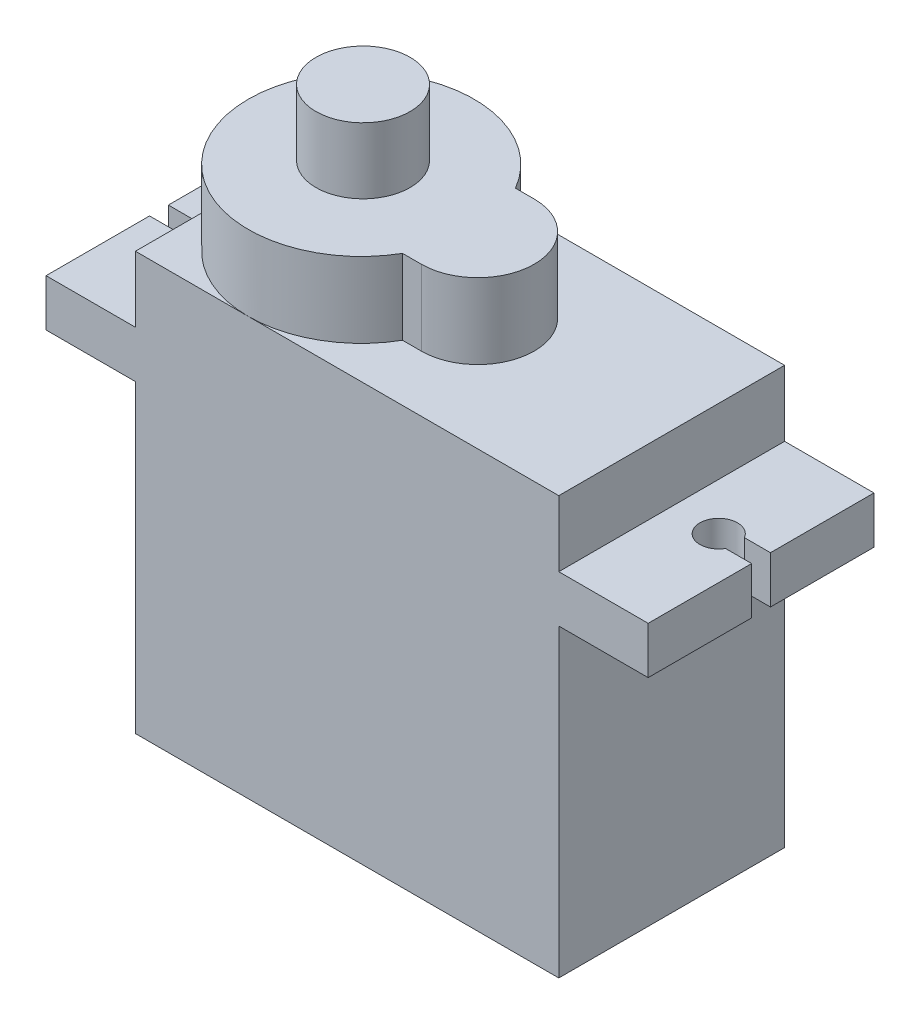
SolidWorks part; units mm, degrees
ref_plane "Front Plane" through (0, 0, 0) normal (0, 0, 1) x (1, 0, 0)
ref_plane "Top Plane" through (0, 0, 0) normal (0, 1, 0) x (1, 0, 0)
ref_plane "Right Plane" through (0, 0, 0) normal (1, 0, 0) x (0, 0, -1)
sketch "Sketch1" plane through (0, 0, 0) normal (0, 0, 1) x (1, 0, 0)
  line L0 (11.25, 0) -> (-11.25, 0)
  line L1 (11.25, 0) -> (11.25, 22.2)
  line L2 (-11.25, 0) -> (-11.25, 22.2)
  line L3 (11.25, 22.2) -> (-11.25, 22.2)
  dimension "D1" = 22.2
  dimension "D2" = 22.5
extrude "Boss-Extrude1" add sketch "Sketch1" along normal mid plane 12
sketch "Sketch2" plane through (0, 22.2, 0) normal (0, 1, 0) x (1, 0, 0)
  line L0 (-11.25, -6) -> (-11.25, 6) construction
  line L1 (11.25, 6) -> (-11.25, 6) construction
  line L2 (11.25, -6) -> (-11.25, -6) construction
  line L3 (0.9462, 3.8912) -> (0.9462, -3.8912) construction
  line L4 (0.9462, 3) -> (-0.0538, 3)
  line L5 (0.9462, -3) -> (-0.0538, -3)
  arc A0 (-0.0538, 3) -> (-0.0538, -3) centre (-5.25, 0) ccw
  arc A3 (0.9462, -3) -> (0.9462, 3) centre (0.9462, 0) ccw
  point P13 (-0.4676, 3.6234)
  point P16 (0, 0)
  point P17 (0, 0)
  dimension "D1" = 3
  dimension "D2" = 1
extrude "Boss-Extrude2" add sketch "Sketch2" along normal blind 4
sketch "Sketch3" plane through (0, 26.2, 0) normal (0, 1, 0) x (1, 0, 0)
  circle A0 centre (-5.3795, 0.2262) radius 2.5
  dimension "D1" = 5
extrude "Boss-Extrude3" add sketch "Sketch3" along normal blind 3.5
sketch "Sketch4" plane through (0, 0, 0) normal (1, 0, 0) x (0, 0, -1)
  line L0 (-6, 18.7) -> (-6, 16.2)
  line L1 (-6, 18.7) -> (6, 18.7)
  line L2 (-6, 16.2) -> (6, 16.2)
  line L3 (6, 18.7) -> (6, 16.2)
  line L4 (-6, 22.2) -> (-6, 0) construction
  line L6 (6, 22.2) -> (3, 22.2) construction
  line L7 (6, 0) -> (6, 22.2) construction
  point P8 (0, 0)
  dimension "D1" = 3.5
  dimension "D2" = 2.5
extrude "Boss-Extrude4" add sketch "Sketch4" along normal mid plane 32
sketch "Sketch5" plane through (0, 18.7, 0) normal (0, 1, 0) x (1, 0, 0)
  line L0 (14.616, 0.5) -> (16, 0.5)
  line L1 (16, 6) -> (16, -6) construction
  line L2 (14.616, -0.5) -> (16, -0.5)
  line L3 (16, 0.5) -> (16, -0.5)
  line L4 (11.25, 6) -> (11.25, -6) construction
  arc A0 (14.616, 0.5) -> (14.616, -0.5) centre (13.75, 0) ccw
  point P1 (12.75, 0)
  point P10 (16, 0)
  dimension "D2" = 1
  dimension "D1" = 1
  dimension "D3" = 1.5
extrude "Cut-Extrude1" cut sketch "Sketch5" against normal up to surface (2.5 mm away) up to face at (13.625, 16.2, 0)
mirror "Mirror1" about plane through (0, 0, 0) normal (1, 0, 0) of "Cut-Extrude1"
